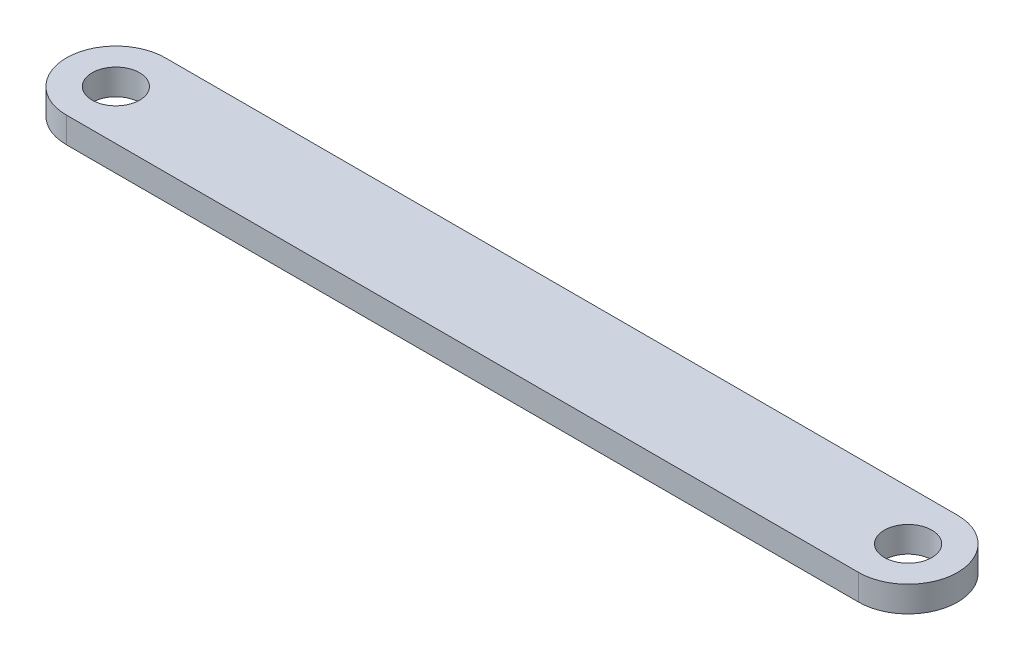
SolidWorks part; units mm, degrees
ref_plane "Płaszczyzna przednia" through (0, 0, 0) normal (0, 0, 1) x (1, 0, 0)
ref_plane "Płaszczyzna górna" through (0, 0, 0) normal (0, 1, 0) x (1, 0, 0)
ref_plane "Płaszczyzna prawa" through (0, 0, 0) normal (1, 0, 0) x (0, 0, -1)
sketch "Szkic1" plane through (0, 0, 0) normal (0, 1, 0) x (1, 0, 0)
  line L0 (0, 0) -> (200, 0) construction
  line L1 (0, 12.5) -> (200, 12.5)
  line L2 (0, -12.5) -> (200, -12.5)
  arc A0 (0, 12.5) -> (0, -12.5) centre (0, 0) ccw
  arc A1 (200, -12.5) -> (200, 12.5) centre (200, 0) ccw
  circle A2 centre (0, 0) radius 6
  circle A3 centre (200, 0) radius 6
  point P3 (100, 0)
  dimension "D3" = 12
  dimension "D1" = 200
  dimension "D2" = 25
extrude "Dodanie-wyciągnięcie1" add sketch "Szkic1" along normal blind 6.5
